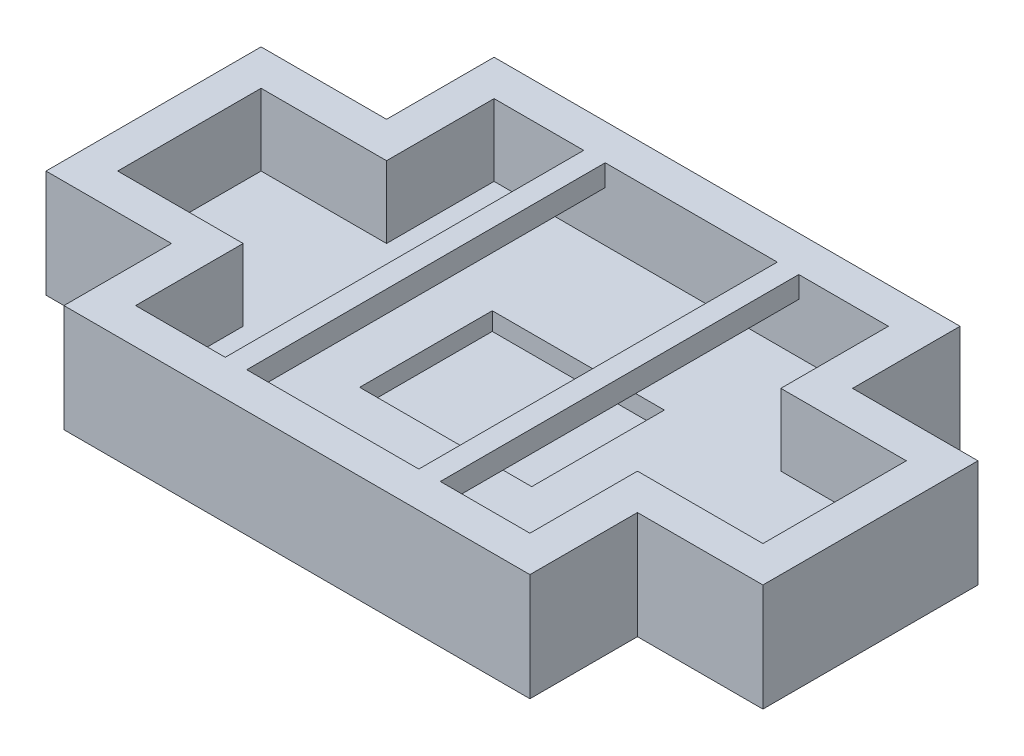
SolidWorks part; units mm, degrees
ref_plane "Front Plane" through (0, 0, 0) normal (0, 0, 1) x (1, 0, 0)
ref_plane "Top Plane" through (0, 0, 0) normal (0, 1, 0) x (1, 0, 0)
ref_plane "Right Plane" through (0, 0, 0) normal (1, 0, 0) x (0, 0, -1)
sketch "Sketch1" plane through (0, 0, 0) normal (0, 1, 0) x (1, 0, 0)
  line L1 (-500, 150) -> (500, 150)
  line L2 (-500, 150) -> (-500, -150)
  line L3 (-500, -150) -> (500, -150)
  line L4 (500, 150) -> (500, -150)
  line L5 (-325, 300) -> (325, 300)
  line L6 (-325, 300) -> (-325, -300)
  line L7 (-325, -300) -> (325, -300)
  line L8 (325, 300) -> (325, -300)
  point P8 (-325, 0)
  point P9 (-500, 0)
  point P11 (0, 150)
  point P12 (0, 300)
  dimension "D1" = 650
  dimension "D2" = 1000
  dimension "D3" = 300
  dimension "D4" = 600
extrude "Boss-Extrude1" add sketch "Sketch1" along normal mid plane 150 contours L8 L1 L6 L3 | L6 L1 L2 L3 | L8 L3 L6 L7 | L1 L8 L3 L4 | L8 L5 L6 L1
sketch "Sketch2" plane through (0, 75, 0) normal (0, 1, 0) x (1, 0, 0)
  line L0 (-120, 0) -> (120, 0) construction
  line L1 (120, -92.5) -> (-120, -92.5)
  line L2 (120, -92.5) -> (120, 92.5)
  line L3 (120, 92.5) -> (-120, 92.5)
  line L4 (-120, -92.5) -> (-120, 92.5)
  dimension "D1" = 240
  dimension "D2" = 185
extrude "Cut-Extrude1" cut sketch "Sketch2" against normal blind 125
sketch "Sketch3" plane through (0, 75, 0) normal (0, 1, 0) x (1, 0, 0)
  line L0 (-325, -150) -> (-325, -300)
  line L1 (-500, 150) -> (-325, 150)
  line L2 (-500, 150) -> (-500, -150)
  line L3 (-500, -150) -> (-325, -150)
  line L4 (500, 150) -> (500, -150)
  line L5 (-325, 300) -> (325, 300)
  line L6 (-325, 300) -> (-325, 150)
  line L7 (-325, -300) -> (325, -300)
  line L8 (325, 300) -> (325, 150)
  line L9 (325, 150) -> (500, 150)
  line L10 (325, -150) -> (325, -300)
  line L11 (325, -150) -> (500, -150)
  line L12 (-450, 100) -> (-275, 100)
  line L13 (-275, 250) -> (-275, 100)
  line L14 (-275, 250) -> (275, 250)
  line L15 (275, 250) -> (275, 100)
  line L16 (275, 100) -> (450, 100)
  line L17 (450, 100) -> (450, -100)
  line L18 (275, -100) -> (450, -100)
  line L19 (275, -100) -> (275, -250)
  line L20 (-275, -250) -> (275, -250)
  line L21 (-275, -100) -> (-275, -250)
  line L22 (-450, -100) -> (-275, -100)
  line L23 (-450, 100) -> (-450, -100)
  dimension "D1" = 50
extrude "Cut-Extrude2" cut sketch "Sketch3" against normal offset from surface (100 mm away) 50 contours L12 L13 L14 L15 L16 L17 L18 L19 L20 L21 L22 L23
sketch "Sketch4" plane through (0, 75, 0) normal (0, 1, 0) x (1, 0, 0)
  line L0 (275, 250) -> (-275, 250) construction
  line L1 (-150, 250) -> (-120, 250)
  line L2 (-150, 250) -> (-150, -250)
  line L3 (-150, -250) -> (-120, -250)
  line L4 (-120, 250) -> (-120, -250)
  line L5 (-275, -250) -> (275, -250) construction
  line L6 (-120, 0) -> (120, 0) construction
  line L7 (150, 250) -> (120, 250)
  line L8 (150, 250) -> (150, -250)
  line L9 (150, -250) -> (120, -250)
  line L10 (120, 250) -> (120, -250)
  dimension "D1" = 30
  dimension "D2" = 240
extrude "Boss-Extrude2" add sketch "Sketch4" against normal blind 30
